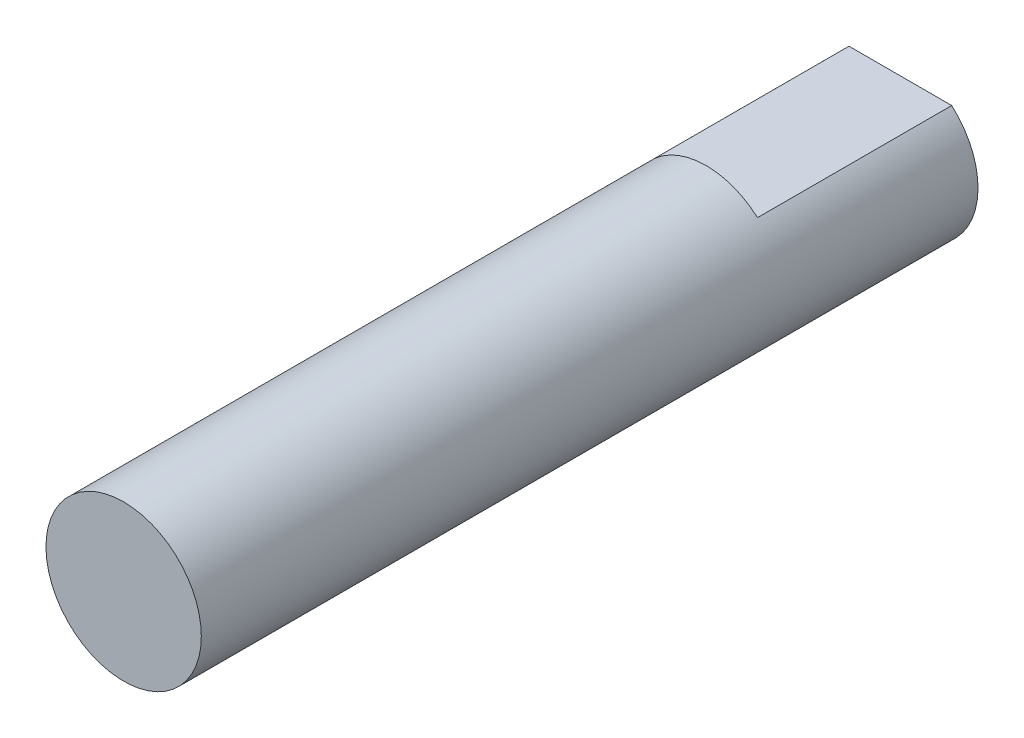
SolidWorks part; units mm, degrees
ref_plane "정면" through (0, 0, 0) normal (0, 0, 1) x (1, 0, 0)
ref_plane "윗면" through (0, 0, 0) normal (0, 1, 0) x (1, 0, 0)
ref_plane "우측면" through (0, 0, 0) normal (1, 0, 0) x (0, 0, -1)
sketch "스케치1" plane through (0, 0, 0) normal (0, 0, 1) x (1, 0, 0)
  circle A0 centre (0, 0) radius 4
  dimension "D1" = 8
extrude "보스-돌출1" add sketch "스케치1" along normal blind 40
sketch "스케치2" plane through (0, 0, 0) normal (0, 0, 1) x (1, 0, 0)
  line L0 (-2.6458, 3) -> (2.6458, 3)
  circle A0 centre (0, 0) radius 4 construction
  arc A1 (-2.6458, 3) -> (2.6458, 3) centre (0, 0) cw
  dimension "D1" = 3
extrude "컷-돌출1" cut sketch "스케치2" along normal blind 10
